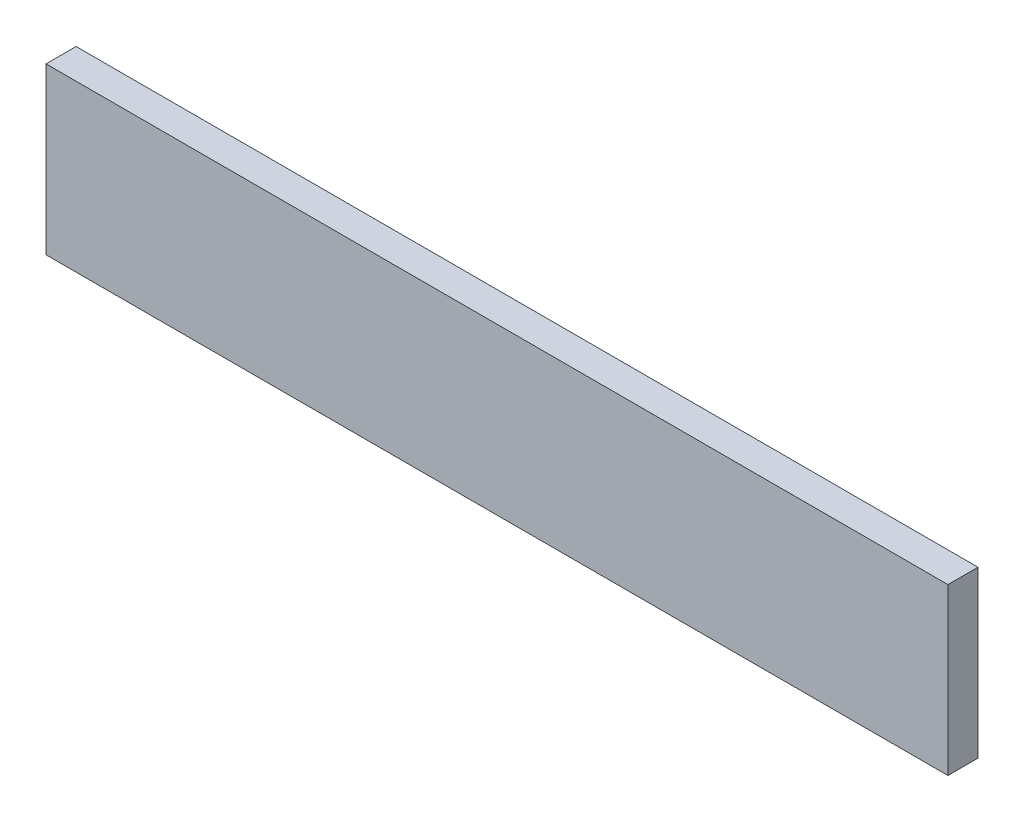
SolidWorks part; units mm, degrees
material "Plywood"
ref_plane "Plan de face" through (0, 0, 0) normal (0, 0, 1) x (1, 0, 0)
ref_plane "Plan de dessus" through (0, 0, 0) normal (0, 1, 0) x (1, 0, 0)
ref_plane "Plan de droite" through (0, 0, 0) normal (1, 0, 0) x (0, 0, -1)
sketch "Esquisse1" plane through (0, 0, 0) normal (0, 0, 1) x (1, 0, 0)
  line L1 (0, 0) -> (60, 0)
  line L2 (0, 0) -> (0, 11)
  line L3 (0, 11) -> (60, 11)
  line L4 (60, 0) -> (60, 11)
  dimension "D1" = 11
  dimension "D2" = 60
extrude "Boss.-Extru.1" add sketch "Esquisse1" along normal blind 2
